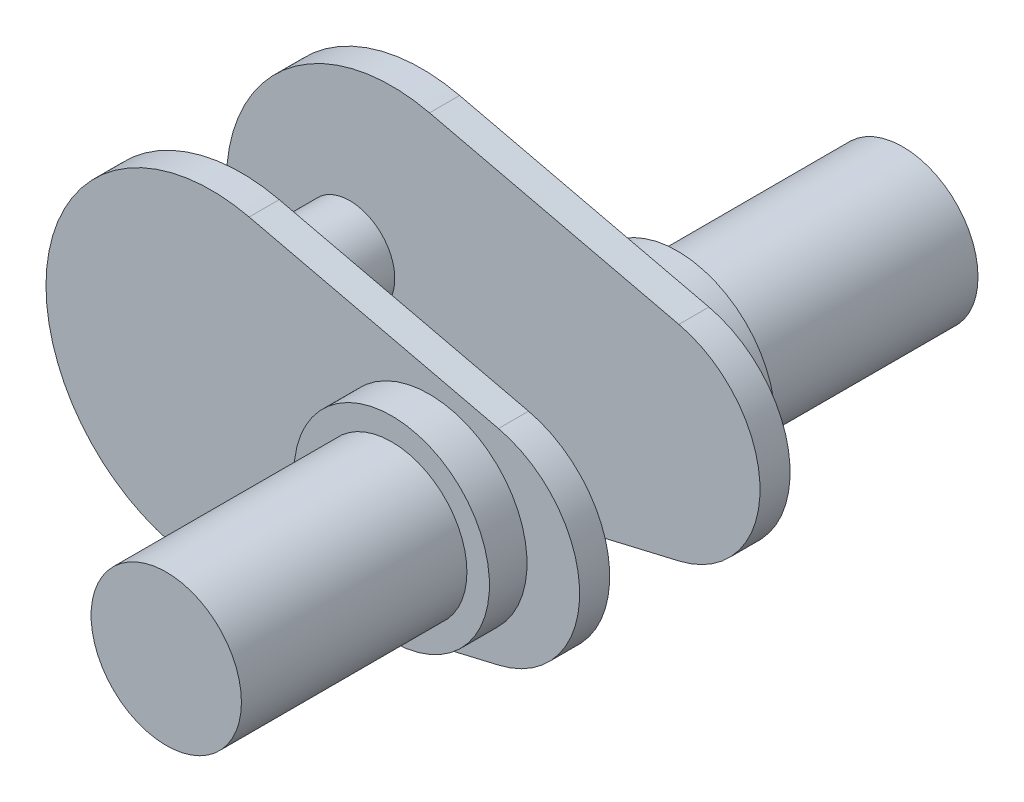
SolidWorks part; units mm, degrees
ref_plane "前视" through (0, 0, 0) normal (0, 0, 1) x (1, 0, 0)
ref_plane "上视" through (0, 0, 0) normal (0, 1, 0) x (1, 0, 0)
ref_plane "右视" through (0, 0, 0) normal (1, 0, 0) x (0, 0, -1)
sketch "草图1" plane through (0, 0, 0) normal (0, 0, 1) x (1, 0, 0)
  circle A0 centre (0, 0) radius 10
extrude "拉伸1" add sketch "草图1" against normal blind 30
sketch "草图2" plane through (0, 0, -30) normal (0, 0, -1) x (-1, 0, 0)
  circle A0 centre (0, 0) radius 13
extrude "拉伸2" add sketch "草图2" along normal blind 5
sketch "草图3" plane through (0, 0, -35) normal (0, 0, -1) x (-1, 0, 0)
  line L0 (-9.2, 13.6294) -> (23.9714, 21.4176)
  line L1 (-9.2, -13.6294) -> (23.9714, -21.4176)
  arc A0 (-9.2, 13.6294) -> (-9.2, -13.6294) centre (-6, 0) ccw
  arc A1 (23.9714, -21.4176) -> (23.9714, 21.4176) centre (29, 0) ccw
  dimension "D1" = 6
  dimension "D2" = 35
  dimension "D3" = 22
  dimension "D4" = 14
extrude "拉伸3" add sketch "草图3" along normal blind 4
sketch "草图5" plane through (0, 0, -39) normal (0, 0, -1) x (-1, 0, 0)
  circle A0 centre (34.5896, 0) radius 6
extrude "拉伸4" add sketch "草图5" along normal blind 10
mirror "镜向2" about plane through (-34.5896, 0, -49) normal (0, 0, -1) of "拉伸4", "拉伸3", "拉伸2", "拉伸1"
